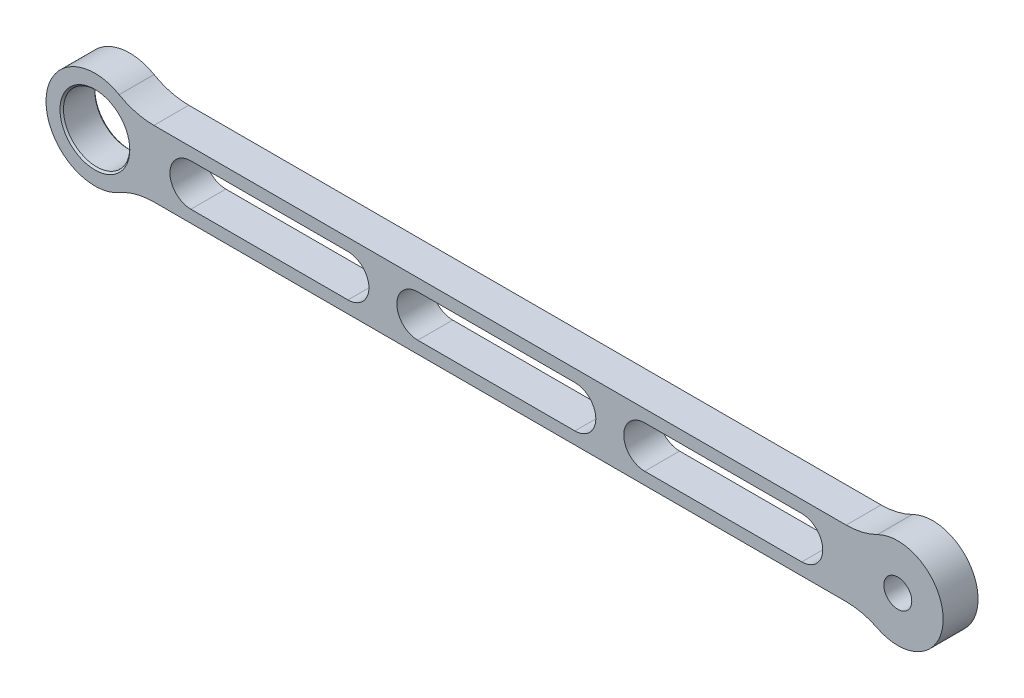
SolidWorks part; units mm, degrees
ref_plane "前视基准面" through (0, 0, 0) normal (0, 0, 1) x (1, 0, 0)
ref_plane "上视基准面" through (0, 0, 0) normal (0, 1, 0) x (1, 0, 0)
ref_plane "右视基准面" through (0, 0, 0) normal (1, 0, 0) x (0, 0, -1)
sketch "草图1" plane through (0, 0, 0) normal (0, 0, 1) x (1, 0, 0)
  line L0 (0, 0) -> (9.5, 0) construction
  line L1 (1.5589, 9.3712) -> (0, 9.5) construction
  line L2 (212.8026, -9.5) -> (16.9041, -9.5)
  line L4 (212.8026, 9.5) -> (16.9041, 9.5)
  line L6 (230, -9.5) -> (228.4411, -9.3712) construction
  line L7 (230, 9.5) -> (228.4411, 9.3712) construction
  line L8 (1.5589, -9.3712) -> (0, -9.5) construction
  line L9 (212.8026, 9.5) -> (215.2098, 9.5)
  line L10 (212.8026, -9.5) -> (215.2098, -9.5)
  line L11 (217, 0) -> (230, 0) construction
  circle A0 centre (0, 0) radius 9.5
  arc A1 (6.9605, 12.1471) -> (6.9605, -12.1471) centre (0, 0) ccw
  circle A2 centre (230, 0) radius 9.5
  arc A6 (6.9605, -12.1471) -> (16.9041, -9.5) centre (16.9041, -29.5) cw
  arc A7 (6.9605, 12.1471) -> (16.9041, 9.5) centre (16.9041, 29.5) ccw
  arc A8 (223.1064, -11.0217) -> (223.1064, 11.0217) centre (230, 0) ccw
  arc A11 (224.1736, -11.6212) -> (224.1736, 11.6212) centre (230, 0) ccw
  arc A12 (215.2098, -9.5) -> (224.1736, -11.6212) centre (215.2098, -29.5) cw
  arc A13 (224.1736, 11.6212) -> (215.2098, 9.5) centre (215.2098, 29.5) cw
  point P7 (115, 0)
  dimension "D1" = 20
  dimension "D2" = 9.5
  dimension "D4" = 230
  dimension "D3" = 9.5
extrude "凸台-拉伸1" add sketch "草图1" along normal blind 10
chamfer "倒角1" distance 0.5 angle 45 2 edges at (9.5, 0, 0) (9.5, 0, 10)
sketch "草图2" plane through (0, 0, 10) normal (0, 0, 1) x (1, 0, 0)
  line L0 (0, 0) -> (32, 0) construction
  line L1 (116.057, 0) -> (116.057, 9.5) construction
  line L2 (215.2098, 9.5) -> (16.9041, 9.5) construction
  line L3 (50, 0) -> (68, 0) construction
  line L4 (137.5, -6) -> (92.5, -6)
  line L6 (137.5, 6) -> (92.5, 6)
  line L9 (202.5, 0) -> (230, 0) construction
  line L10 (27.5, -6) -> (72.5, -6)
  line L12 (27.5, 6) -> (72.5, 6)
  line L14 (50, 0) -> (70.7692, 4.1538) construction
  line L15 (29.2308, 4.1538) -> (70.7692, -4.1538) construction
  line L16 (157.5, -6) -> (202.5, -6)
  line L18 (157.5, 6) -> (202.5, 6)
  line L22 (78.5, 0) -> (198, 0) construction
  arc A0 (27.5, 6) -> (27.5, -6) centre (27.5, 0) ccw
  arc A1 (72.5, -6) -> (72.5, 6) centre (72.5, 0) ccw
  arc A2 (92.5, 6) -> (92.5, -6) centre (92.5, 0) ccw
  arc A3 (137.5, -6) -> (137.5, 6) centre (137.5, 0) ccw
  arc A4 (157.5, 6) -> (157.5, -6) centre (157.5, 0) ccw
  arc A5 (202.5, -6) -> (202.5, 6) centre (202.5, 0) ccw
  point P12 (50, 0)
  point P17 (180, 0)
  dimension "D1" = 12
  dimension "D2" = 12
  dimension "D3" = 12
extrude "切除-拉伸2" cut sketch "草图2" against normal blind 10
sketch "草图3" plane through (0, 0, 10) normal (0, 0, 1) x (1, 0, 0)
  circle A0 centre (230, 0) radius 4
  circle A1 centre (230, 0) radius 9.5
extrude "凸台-拉伸2" add sketch "草图3" against normal blind 10
sketch "草图4" plane through (0, 0, 10) normal (0, 0, 1) x (1, 0, 0)
  circle A0 centre (230, 0) radius 6
extrude "切除-拉伸3" cut sketch "草图4" against normal blind 10
sketch "草图5" plane through (0, 0, 10) normal (0, 0, 1) x (1, 0, 0)
  circle A0 centre (230, 0) radius 6
  circle A1 centre (230, 0) radius 4
extrude "凸台-拉伸3" add sketch "草图5" against normal blind 10
